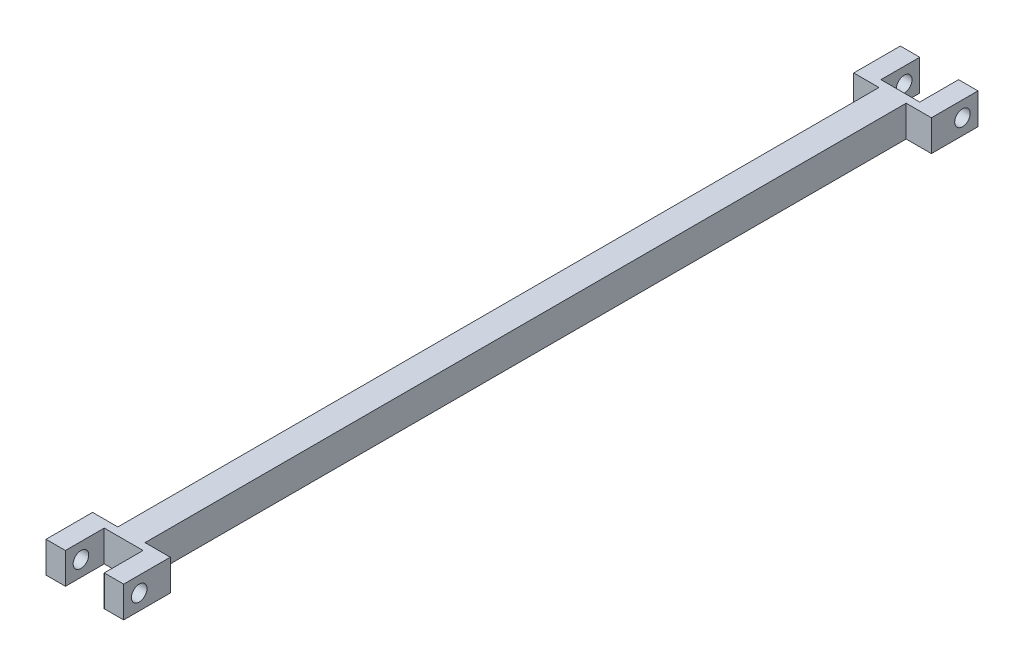
SolidWorks part; units mm, degrees
ref_plane "Płaszczyzna przednia" through (0, 0, 0) normal (0, 0, 1) x (1, 0, 0)
ref_plane "Płaszczyzna górna" through (0, 0, 0) normal (0, 1, 0) x (1, 0, 0)
ref_plane "Płaszczyzna prawa" through (0, 0, 0) normal (1, 0, 0) x (0, 0, -1)
sketch "Szkic1" plane through (0, 0, 0) normal (0, 0, 1) x (1, 0, 0)
  line L1 (0, 0) -> (35, 0)
  line L2 (0, 0) -> (0, 40)
  line L3 (0, 40) -> (35, 40)
  line L4 (35, 0) -> (35, 40)
  dimension "D1" = 35
  dimension "D2" = 40
extrude "Dodanie-wyciągnięcie1" add sketch "Szkic1" along normal blind 980
ref_plane "Płaszczyzna1" through (0, 0, 980) normal (0, 0, 1) x (1, 0, 0)
sketch "Szkic2" plane through (0, 0, 980) normal (0, 0, 1) x (1, 0, 0)
  line L0 (35, 40) -> (0, 40) construction
  line L1 (-32.5, 40) -> (67.5, 40)
  line L2 (-32.5, 40) -> (-32.5, 0)
  line L3 (-32.5, 0) -> (67.5, 0)
  line L4 (67.5, 40) -> (67.5, 0)
  line L5 (0, 0) -> (35, 0) construction
  line L6 (0, 40) -> (35, 0) construction
  line L7 (35, 40) -> (0, 0) construction
  point P16 (17.5, 20)
  dimension "D1" = 100
  dimension "D2" = 50
extrude "Dodanie-wyciągnięcie2" add sketch "Szkic2" along normal blind 10
ref_plane "Płaszczyzna2" through (0, 0, 990) normal (0, 0, 1) x (1, 0, 0)
sketch "Szkic3" plane through (0, 0, 990) normal (0, 0, 1) x (1, 0, 0)
  line L0 (-7.5, 40) -> (-7.5, 0)
  line L1 (67.5, 40) -> (-32.5, 40) construction
  line L2 (-32.5, 0) -> (67.5, 0) construction
  line L3 (42.5, 40) -> (42.5, 0)
  line L4 (-32.5, 40) -> (-32.5, 0) construction
  line L5 (67.5, 0) -> (67.5, 40) construction
  line L6 (67.5, 0) -> (67.5, 40)
  line L7 (-32.5, 0) -> (-7.5, 0)
  line L8 (67.5, 40) -> (42.5, 40)
  line L9 (-32.5, 40) -> (-32.5, 0)
  line L10 (-7.5, 40) -> (-32.5, 40)
  line L11 (42.5, 0) -> (67.5, 0)
  dimension "D1" = 25
  dimension "D2" = 25
extrude "Dodanie-wyciągnięcie3" add sketch "Szkic3" along normal blind 50
ref_plane "Płaszczyzna3" through (167.5, 0, 0) normal (1, 0, 0) x (0, 0, -1)
sketch "Szkic4" plane through (167.5, 0, 0) normal (1, 0, 0) x (0, 0, -1)
  line L0 (-980, 0) -> (-980, 40) construction
  line L1 (-1040, 40) -> (-980, 40) construction
  line L2 (-1040, 0) -> (-980, 0) construction
  line L3 (-1040, 0) -> (-1040, 40) construction
  line L4 (-980, 0) -> (-980, 40)
  line L5 (-1040, 40) -> (-980, 40)
  line L6 (-1040, 0) -> (-980, 0)
  line L7 (-1040, 0) -> (-1040, 40)
  circle A0 centre (-1020, 20) radius 10
  point P2 (0, 0)
  point P3 (0, 0)
  dimension "D1" = 20
  dimension "D2" = 20
  dimension "D3" = 20
extrude "Wytnij-wyciągnięcie3" cut sketch "Szkic4" against normal through all contours A0
ref_plane "Płaszczyzna4" through (0, 0, 490) normal (0, 0, -1) x (-1, 0, 0)
mirror "Lustro1" about plane through (0, 0, 490) normal (0, 0, -1) of "Wytnij-wyciągnięcie3", "Dodanie-wyciągnięcie2", "Dodanie-wyciągnięcie3"
